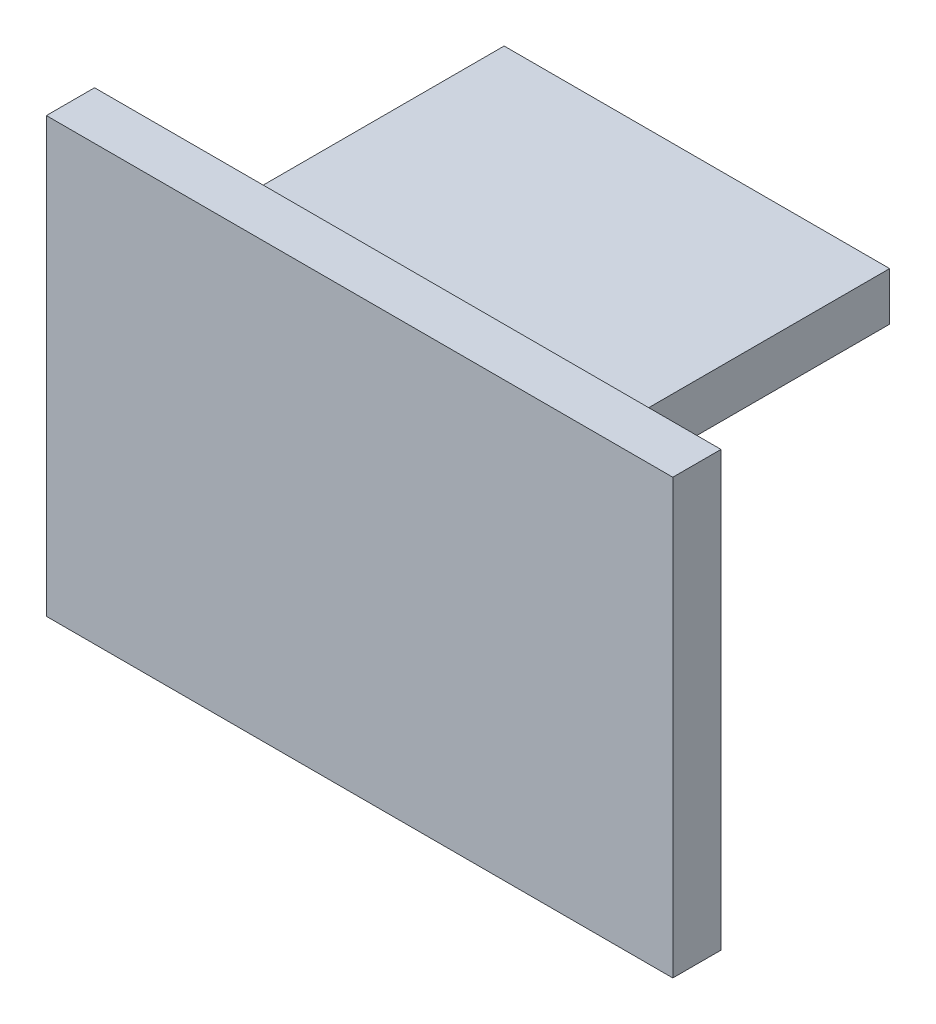
SolidWorks part; units mm, degrees
ref_plane "Front Plane" through (0, 0, 0) normal (0, 0, 1) x (1, 0, 0)
ref_plane "Top Plane" through (0, 0, 0) normal (0, 1, 0) x (1, 0, 0)
ref_plane "Right Plane" through (0, 0, 0) normal (1, 0, 0) x (0, 0, -1)
sketch "Sketch1" plane through (0, 0, 0) normal (0, 0, 1) x (1, 0, 0)
  line L0 (-13, 0) -> (13, 0)
  line L1 (13, 0) -> (13, 18)
  line L2 (13, 18) -> (-13, 18)
  line L3 (-13, 18) -> (-13, 0)
  point P4 (0, 0)
  dimension "D1" = 13
  dimension "D2" = 18
extrude "Boss-Extrude1" add sketch "Sketch1" along normal blind 2
sketch "Sketch2" plane through (0, 0, 0) normal (0, 0, -1) x (-1, 0, 0)
  line L2 (-8, 16) -> (8, 16)
  line L3 (8, 16) -> (8, 14)
  line L4 (8, 14) -> (-8, 14)
  line L5 (-8, 14) -> (-8, 16)
  point P8 (0, 16)
  dimension "D1" = 8
  dimension "D2" = 14
  dimension "D3" = 2
  dimension "D4" = 16
extrude "Boss-Extrude2" add sketch "Sketch2" along normal blind 12
